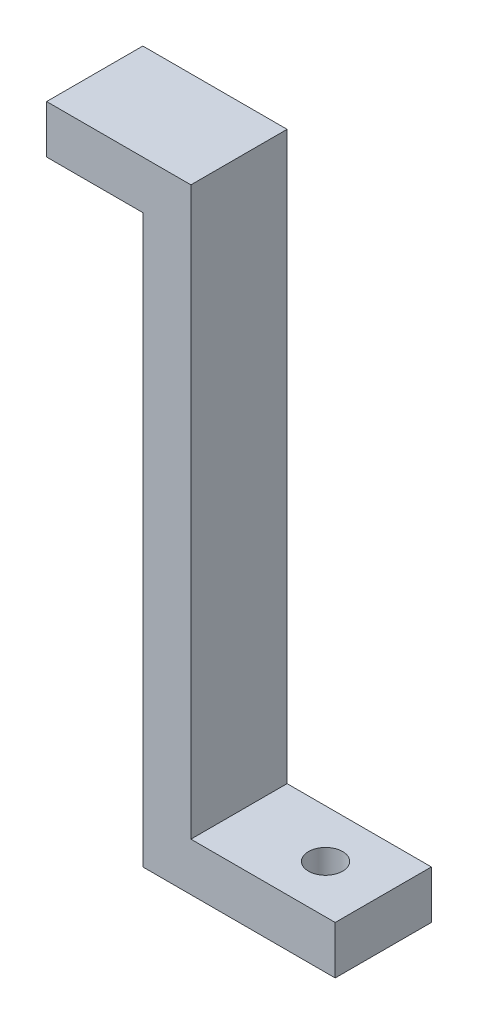
SolidWorks part; units mm, degrees
ref_plane "Front Plane" through (0, 0, 0) normal (0, 0, 1) x (1, 0, 0)
ref_plane "Top Plane" through (0, 0, 0) normal (0, 1, 0) x (1, 0, 0)
ref_plane "Right Plane" through (0, 0, 0) normal (1, 0, 0) x (0, 0, -1)
sketch "Sketch1" plane through (0, 0, 0) normal (0, 0, 1) x (1, 0, 0)
  line L0 (0, 0) -> (0, 5)
  line L1 (0, 5) -> (-15, 5)
  line L2 (-15, 5) -> (-15, 63.912)
  line L3 (-15, 63.912) -> (-30, 63.912)
  line L4 (-30, 63.912) -> (-30, 58.912)
  line L5 (-30, 58.912) -> (-20, 58.912)
  line L6 (-20, 58.912) -> (-20, 0)
  line L7 (-20, 0) -> (0, 0)
  dimension "D1" = 5
  dimension "D2" = 5
  dimension "D3" = 5
  dimension "D4" = 63.912
  dimension "D5" = 30
  dimension "D6" = 15
extrude "Boss-Extrude1" add sketch "Sketch1" along normal blind 10
sketch "Sketch2" plane through (0, 5, 0) normal (0, 1, 0) x (1, 0, 0)
  line L0 (-6, -10) -> (-6, 0) construction
  line L1 (0, -10) -> (-15, -10) construction
  line L2 (0, 0) -> (-15, 0) construction
  line L3 (0, -10) -> (0, 0) construction
  line L4 (-30, -10) -> (-30, 0) construction
  circle A0 centre (-6, -5) radius 1.775
  dimension "D1" = 3.55
  dimension "D2" = 6
  dimension "D3" = 24
extrude "Cut-Extrude1" cut sketch "Sketch2" against normal through all
